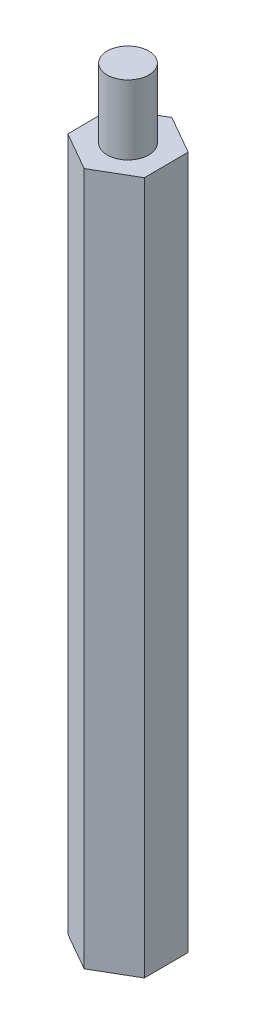
SolidWorks part; units mm, degrees
ref_plane "Alzado" through (0, 0, 0) normal (0, 0, 1) x (1, 0, 0)
ref_plane "Planta" through (0, 0, 0) normal (0, 1, 0) x (1, 0, 0)
ref_plane "Vista lateral" through (0, 0, 0) normal (1, 0, 0) x (0, 0, -1)
sketch "Croquis1" plane through (0, 0, 0) normal (0, 1, 0) x (1, 0, 0)
  line L1 (2.7435, 1.599) -> (-0.013, 3.1754)
  line L2 (-0.013, 3.1754) -> (-2.7565, 1.5764)
  line L3 (-2.7565, 1.5764) -> (-2.7435, -1.599)
  line L4 (-2.7435, -1.599) -> (0.013, -3.1754)
  line L5 (0.013, -3.1754) -> (2.7565, -1.5764)
  line L6 (2.7565, -1.5764) -> (2.7435, 1.599)
  circle A0 centre (0, 0) radius 2.75 construction
  dimension "D1" = 5.5
extrude "Saliente-Extruir1" add sketch "Croquis1" along normal blind 50
sketch "Croquis2" plane through (0, 50, 0) normal (0, 1, 0) x (1, 0, 0)
  circle A0 centre (0, 0) radius 1.5
  dimension "D1" = 3
extrude "Saliente-Extruir2" add sketch "Croquis2" along normal blind 5
sketch "Croquis3" plane through (0, 55, 0) normal (0, 1, 0) x (1, 0, 0)
  point P0 (0, 0)
